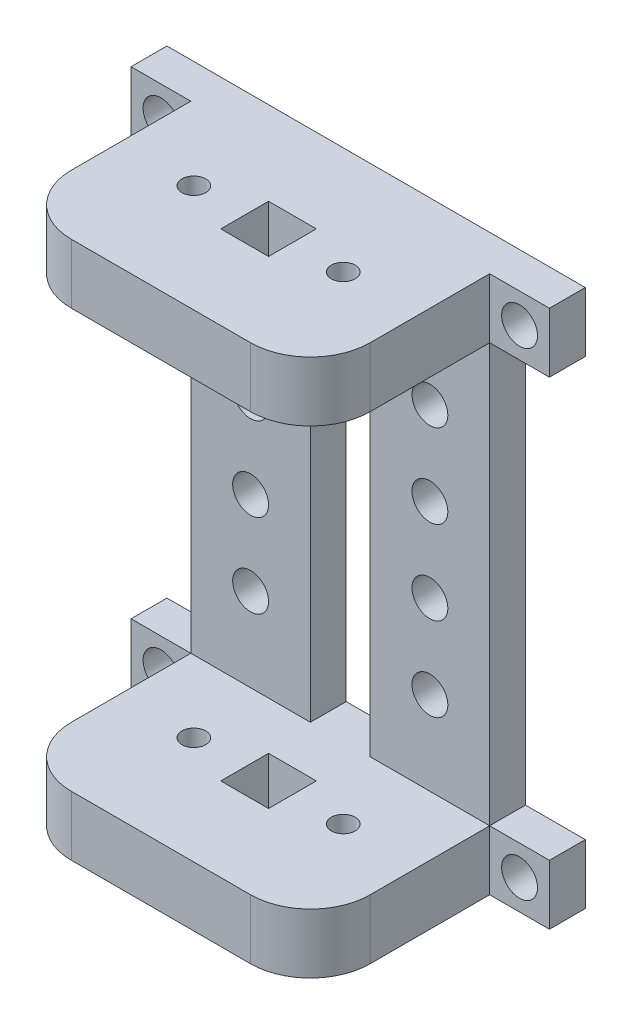
SolidWorks part; units mm, degrees
ref_plane "Plano frontal" through (0, 0, 0) normal (0, 0, 1) x (1, 0, 0)
ref_plane "Plano superior" through (0, 0, 0) normal (0, 1, 0) x (1, 0, 0)
ref_plane "Plano direito" through (0, 0, 0) normal (1, 0, 0) x (0, 0, -1)
sketch "Esboço1" plane through (0, 0, 0) normal (0, 0, 1) x (1, 0, 0)
  line L0 (-24.4304, 7.0667) -> (10.5696, 7.0667)
  line L1 (-24.4304, 7.0667) -> (-24.4304, 2.0667)
  line L2 (10.5696, -37.9333) -> (-24.4304, -37.9333)
  line L3 (-24.4304, 2.0667) -> (-19.4304, 2.0667)
  line L4 (-19.4304, 2.0667) -> (-19.4304, -32.9333)
  line L5 (-19.4304, -32.9333) -> (-24.4304, -32.9333)
  line L6 (-24.4304, -32.9333) -> (-24.4304, -37.9333)
  line L7 (10.5696, -37.9333) -> (10.5696, -32.9333)
  line L8 (10.5696, -32.9333) -> (5.5696, -32.9333)
  line L9 (5.5696, -32.9333) -> (5.5696, 2.0667)
  line L10 (5.5696, 2.0667) -> (10.5696, 2.0667)
  line L11 (10.5696, 2.0667) -> (10.5696, 7.0667)
  line L12 (-9.4304, 2.0667) -> (-9.4304, -32.9333)
  line L13 (-9.4304, -32.9333) -> (-4.4304, -32.9333)
  line L14 (-4.4304, -32.9333) -> (-4.4304, 2.0667)
  line L15 (-4.4304, 2.0667) -> (-9.4304, 2.0667)
  circle A0 centre (-14.4304, -4.9333) radius 1.5
  circle A1 centre (-14.4304, -11.9333) radius 1.5
  circle A2 centre (-14.4304, -18.9333) radius 1.5
  circle A3 centre (0.5696, -4.9333) radius 1.5
  circle A4 centre (0.5696, -18.9333) radius 1.5
  circle A5 centre (0.5696, -25.9333) radius 1.5
  circle A6 centre (-14.4304, -25.9333) radius 1.5
  circle A7 centre (0.5696, -11.9333) radius 1.5
  circle A8 centre (-21.9304, 4.5667) radius 1.5
  circle A9 centre (8.0696, 4.5667) radius 1.5
  circle A10 centre (-21.9304, -35.4333) radius 1.5
  circle A11 centre (8.0696, -35.4333) radius 1.5
  dimension "D13" = 3
  dimension "D1" = 35
  dimension "D2" = 10
  dimension "D3" = 10
  dimension "D4" = 5
  dimension "D5" = 5
  dimension "D6" = 5
  dimension "D7" = 5
  dimension "D8" = 5
  dimension "D9" = 5
  dimension "D10" = 5
  dimension "D11" = 10
  dimension "D12" = 35
  dimension "D14" = 7
  dimension "D15" = 7
  dimension "D16" = 7
  dimension "D17" = 7
  dimension "D18" = 45
  dimension "D19" = 5
  dimension "D20" = 5
  dimension "D21" = 5
  dimension "D22" = 5
  dimension "D23" = 5
  dimension "D24" = 5
  dimension "D25" = 5
  dimension "D26" = 7
  dimension "D27" = 7
  dimension "D28" = 7
  dimension "D29" = 7
  dimension "D30" = 5
  dimension "D31" = 2.5
  dimension "D32" = 2.5
  dimension "D33" = 2.5
  dimension "D34" = 2.5
  dimension "D35" = 2.5
  dimension "D36" = 2.5
  dimension "D37" = 2.5
  dimension "D38" = 2.5
extrude "Ressalto-extrusão1" add sketch "Esboço1" against normal blind 3
sketch "Esboço2" plane through (0, 0, 0) normal (0, 0, 1) x (1, 0, 0)
  line L0 (-19.4304, 2.0667) -> (-19.4304, 7.0667)
  line L1 (10.5696, 7.0667) -> (-24.4304, 7.0667) construction
  line L2 (5.5696, 2.0667) -> (-19.4304, 2.0667)
  line L3 (5.5696, 2.0667) -> (5.5696, 7.0667)
  line L4 (5.5696, 7.0667) -> (-19.4304, 7.0667)
  line L5 (-19.4304, -32.9333) -> (-19.4304, -37.9333)
  line L6 (-24.4304, -37.9333) -> (10.5696, -37.9333) construction
  line L7 (-19.4304, -37.9333) -> (5.5696, -37.9333)
  line L8 (5.5696, -37.9333) -> (5.5696, -32.9333)
  line L9 (5.5696, -32.9333) -> (-19.4304, -32.9333)
extrude "Ressalto-extrusão2" add sketch "Esboço2" along normal blind 15
fillet "Filete5" radius 5 1 edges at (5.5696, -35.4333, 15)
fillet "Filete6" radius 5 1 edges at (-19.4304, -35.4333, 15)
fillet "Filete7" radius 5 2 edges at (-19.4304, 4.5667, 15)
fillet "Filete8" radius 5 2 edges at (5.5696, 4.5667, 15)
sketch "Esboço3" plane through (0, -37.9333, 0) normal (0, -1, 0) x (-1, 0, 0)
  line L0 (19.4304, -10) -> (19.4304, 0) construction
  line L1 (-5.5696, -10) -> (-5.5696, 0) construction
  line L2 (14.4304, -15) -> (-0.5696, -15) construction
  line L5 (8.9304, -8) -> (4.9304, -8)
  line L6 (4.9304, -8) -> (4.9304, -4)
  line L7 (4.9304, -4) -> (8.9304, -4)
  line L8 (8.9304, -4) -> (8.9304, -8)
  circle A0 centre (13.1804, -6) radius 1
  circle A1 centre (0.6804, -6) radius 1
  dimension "D7" = 2
  dimension "D8" = 2
  dimension "D9" = 10.5
  dimension "D1" = 6.25
  dimension "D2" = 4
  dimension "D3" = 4
  dimension "D4" = 6.25
  dimension "D5" = 9
  dimension "D6" = 7
extrude "Corte-extrusão1" cut sketch "Esboço3" against normal blind 5
sketch "Esboço4" plane through (0, 7.0667, 0) normal (0, 1, 0) x (1, 0, 0)
  line L0 (-8.9304, -4) -> (-8.9304, -8)
  line L1 (-8.9304, -8) -> (-4.9304, -8)
  line L2 (-4.9304, -8) -> (-4.9304, -4)
  line L3 (-4.9304, -4) -> (-8.9304, -4)
  line L4 (10.5696, 3) -> (-24.4304, 3) construction
  line L6 (-19.4304, -10) -> (-19.4304, 0) construction
  line L7 (5.5696, -10) -> (5.5696, 0) construction
  circle A0 centre (-13.1804, -6) radius 1
  circle A1 centre (-0.6804, -6) radius 1
  dimension "D1" = 2
  dimension "D2" = 9
  dimension "D3" = 9
  dimension "D4" = 6.25
  dimension "D5" = 6.25
  dimension "D6" = 10.5
  dimension "D7" = 7
  dimension "D8" = 4
  dimension "D9" = 4
extrude "Corte-extrusão2" cut sketch "Esboço4" against normal blind 5
